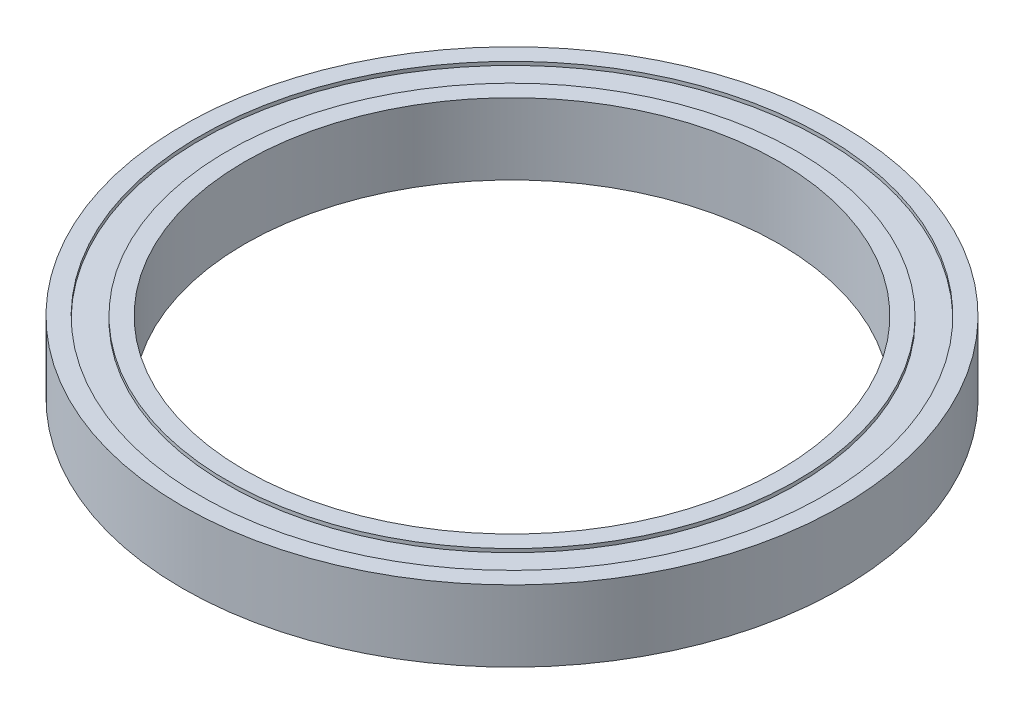
SolidWorks part; units mm, degrees
ref_plane "前视基准面" through (0, 0, 0) normal (0, 0, 1) x (1, 0, 0)
ref_plane "上视基准面" through (0, 0, 0) normal (0, 1, 0) x (1, 0, 0)
ref_plane "右视基准面" through (0, 0, 0) normal (1, 0, 0) x (0, 0, -1)
sketch "草图1" plane through (0, 0, 0) normal (1, 0, 0) x (0, 0, -1)
  line L0 (0, 0) -> (16.75, 0) construction
  line L1 (15, 2) -> (16, 2)
  line L3 (15, 2) -> (15, -2)
  line L5 (18.5, 2) -> (18.5, -2)
  line L6 (15, 2) -> (18.5, -2) construction
  line L7 (15, -2) -> (18.5, 2) construction
  line L8 (16, 2) -> (16, 1.8)
  line L9 (16, 1.8) -> (17.5003, 1.8)
  line L10 (17.5003, 1.8) -> (17.5003, 2)
  line L11 (17.5003, 2) -> (18.5, 2)
  line L12 (15, -2) -> (16, -2)
  line L13 (16, -2) -> (16, -1.8)
  line L14 (16, -1.8) -> (17.5003, -1.8)
  line L15 (17.5003, -1.8) -> (17.5003, -2)
  line L16 (17.5003, -2) -> (18.5, -2)
  line L17 (0, -4.3804) -> (0, 4.8103) construction
  dimension "D1" = 4
  dimension "D2" = 3.5
  dimension "D3" = 16.75
  dimension "D4" = 1
  dimension "D5" = 0.2
  dimension "D6" = 0.9997
revolve "旋转1" add sketch "草图1" angle 360 about L17
